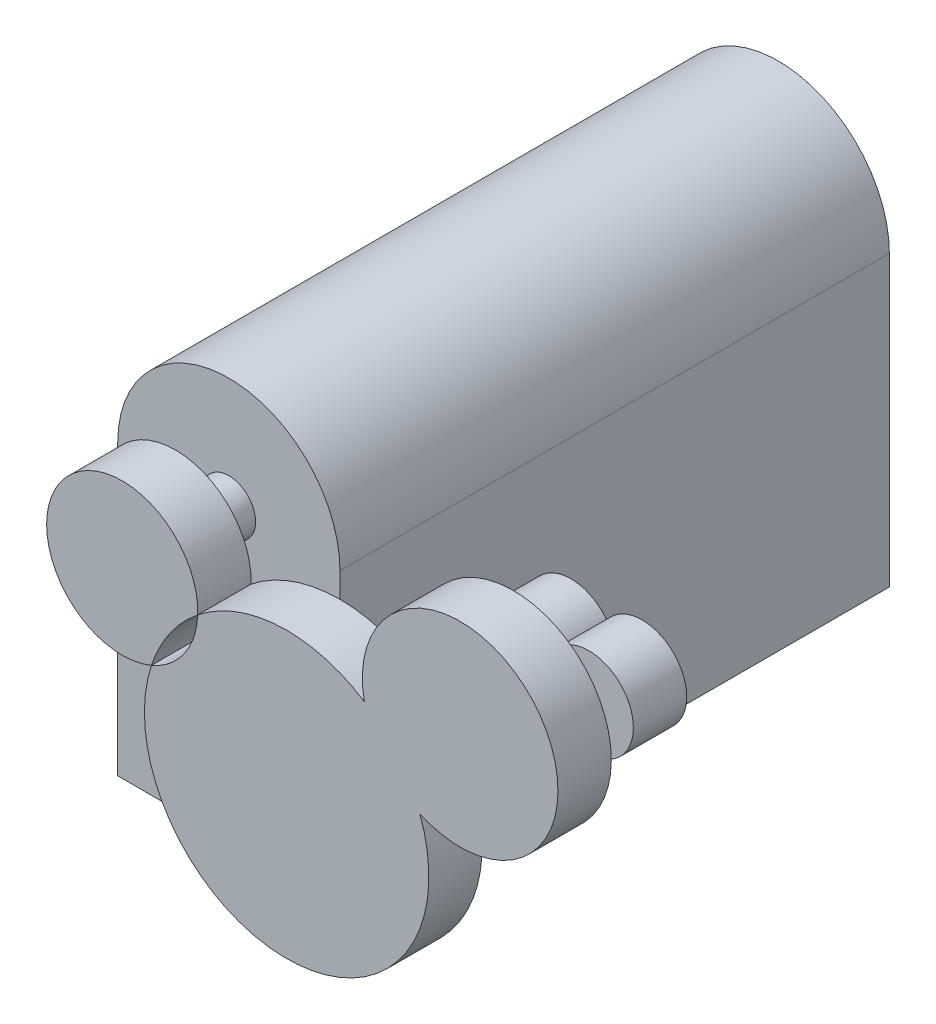
SolidWorks part; units mm, degrees
ref_plane "Front Plane" through (0, 0, 0) normal (0, 0, 1) x (1, 0, 0)
ref_plane "Top Plane" through (0, 0, 0) normal (0, 1, 0) x (1, 0, 0)
ref_plane "Right Plane" through (0, 0, 0) normal (1, 0, 0) x (0, 0, -1)
sketch "Sketch6" plane through (0, 0, 0) normal (0, 0, 1) x (1, 0, 0)
  line L0 (-6.25, 0) -> (-6.25, -16.25)
  line L1 (-6.25, -16.25) -> (6.25, -16.25)
  line L2 (6.25, -16.25) -> (6.25, 0)
  arc A0 (6.25, 0) -> (-6.25, 0) centre (0, 0) ccw
  dimension "D1" = 12.5
  dimension "D2" = 16.25
extrude "Boss-Extrude7" add sketch "Sketch6" against normal blind 30.9
sketch "Sketch7" plane through (0, 0, 0) normal (0, 0, 1) x (1, 0, 0)
  circle A0 centre (0, 0) radius 1.5
  dimension "D1" = 3
extrude "Boss-Extrude8" add sketch "Sketch7" along normal blind 3
sketch "Sketch8" plane through (0, 0, 3) normal (0, 0, 1) x (1, 0, 0)
  line L3 (-6.25, 0) -> (-6.25, -16.25) construction
  circle A0 centre (0, 0) radius 4.25
  circle A1 centre (9.25, -6.4031) radius 8
  circle A2 centre (19.0098, 1.4069) radius 5.5
  circle M3 centre (0, 0) radius 1.5
  dimension "D1" = 8.5
  dimension "D2" = 16
  dimension "D5" = 11
  dimension "D3" = 11.25
  dimension "D4" = 9.25
  dimension "D6" = 12.5
  dimension "D7" = 7.81
extrude "Boss-Extrude9" add sketch "Sketch8" along normal blind 3 contours A1 A0 M3 | A0 A1 | M3 | A2
sketch "Sketch9" plane through (0, 0, 3) normal (0, 0, -1) x (-1, 0, 0)
  circle A0 centre (-9.25, -6.4031) radius 1
  dimension "D1" = 2
extrude "Boss-Extrude10" add sketch "Sketch9" along normal blind 11.773
ref_plane "Plane3" through (0, 0, -7) normal (0, 0, -1) x (-1, 0, 0)
sketch "Sketch10" plane through (0, 0, -7) normal (0, 0, -1) x (-1, 0, 0)
  arc A0 (-11.25, -7.9031) -> (-11.25, -4.9031) centre (-9.25, -6.4031) ccw
  arc A1 (-11.25, -4.9031) -> (-11.25, -7.9031) centre (-13.25, -6.4031) ccw
  dimension "D1" = 5
  dimension "D2" = 5
  dimension "D3" = 4
extrude "Boss-Extrude11" add sketch "Sketch10" along normal blind 3
